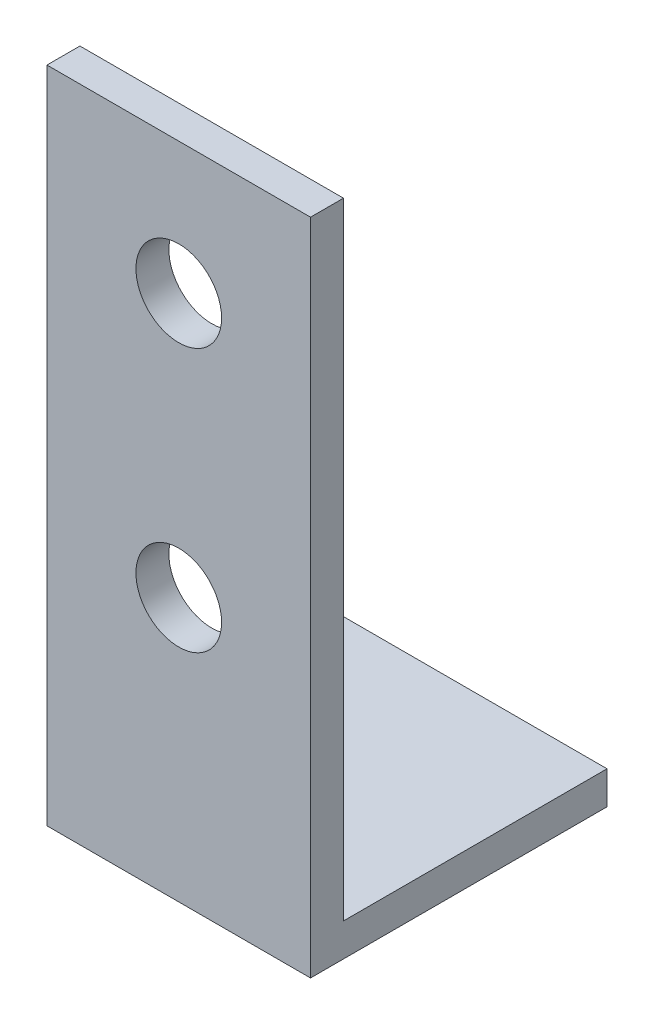
SolidWorks part; units mm, degrees
ref_plane "前基準面" through (0, 0, 0) normal (0, 0, 1) x (1, 0, 0)
ref_plane "上基準面" through (0, 0, 0) normal (0, 1, 0) x (1, 0, 0)
ref_plane "右基準面" through (0, 0, 0) normal (1, 0, 0) x (0, 0, -1)
sketch "草圖1" plane through (0, 0, 0) normal (1, 0, 0) x (0, 0, -1)
  line L0 (0, 0) -> (9, 0)
  line L1 (9, 0) -> (9, 1)
  line L2 (9, 1) -> (1, 1)
  line L3 (1, 1) -> (1, 20)
  line L4 (1, 20) -> (0, 20)
  line L5 (0, 20) -> (0, 0)
  dimension "D1" = 1
  dimension "D2" = 1
  dimension "D3" = 20
  dimension "D4" = 9
extrude "填料-伸長1" add sketch "草圖1" along normal blind 8
sketch "草圖2" plane through (0, 0, 0) normal (0, 0, 1) x (1, 0, 0)
  line L0 (4, 8) -> (4, 0) construction
  line L1 (8, 0) -> (0, 0) construction
  line L2 (8, 20) -> (0, 20) construction
  circle A0 centre (4, 16) radius 1.3
  circle A1 centre (4, 8) radius 1.3
  point P4 (0, 0)
  dimension "D1" = 2.6
  dimension "D2" = 4
  dimension "D3" = 8
extrude "除料-伸長1" cut sketch "草圖2" against normal through all
